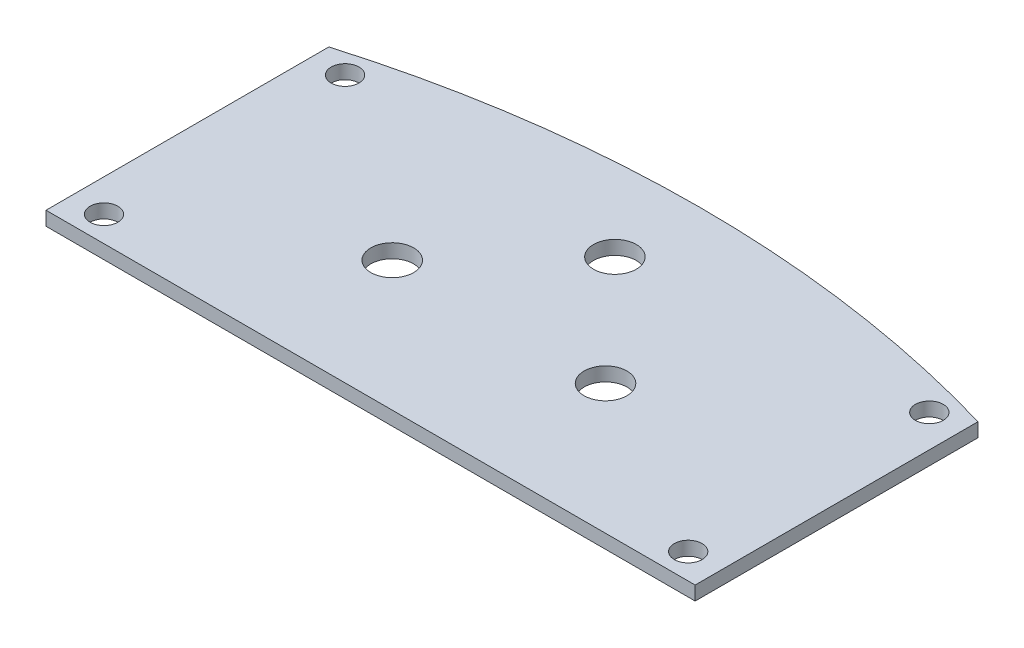
SolidWorks part; units mm, degrees
ref_plane "Front Plane" through (0, 0, 0) normal (0, 0, 1) x (1, 0, 0)
ref_plane "Top Plane" through (0, 0, 0) normal (0, 1, 0) x (1, 0, 0)
ref_plane "Right Plane" through (0, 0, 0) normal (1, 0, 0) x (0, 0, -1)
sketch "Sketch1" plane through (0, 0, 0) normal (0, 1, 0) x (1, 0, 0)
  line L1 (70, 28.5) -> (70, -32.5)
  line L3 (-70, -32.5) -> (-70, 28.5)
  line L4 (-70, -32.5) -> (70, -32.5)
  arc A0 (-70, 28.5) -> (70, 28.5) centre (0, -210.1566) cw
  dimension "D1" = 61
  dimension "D2" = 140
  dimension "D3" = 61
  dimension "D4" = 70
extrude "Boss-Extrude1" add sketch "Sketch1" along normal blind 3
sketch "Sketch3" plane through (0, 3, 0) normal (0, 1, 0) x (1, 0, 0)
  line L0 (0, 43.0385) -> (0, -46.4553) construction
  line L1 (-70, -32.5) -> (70, -32.5) construction
  circle A13 centre (-63, 25) radius 3
  circle A14 centre (-63, -27) radius 3
  circle A15 centre (63, 25) radius 3
  circle A16 centre (63, -27) radius 3
  dimension "D13" = 89.4937
  dimension "D15" = 52
  dimension "D16" = 52
  dimension "D2" = 5.5
extrude "Cut-Extrude1" cut sketch "Sketch3" against normal blind 10
sketch "Sketch4" plane through (0, 0, 0) normal (0, -1, 0) x (-1, 0, 0)
  line L0 (70, -32.5) -> (-70, -32.5) construction
  line L1 (70, 28.5) -> (70, -32.5) construction
  circle A0 centre (23.33, -4.5) radius 4.62
  circle A1 centre (-22.67, -4.5) radius 4.62
  circle A2 centre (-0.056, 20.1385) radius 4.62
  point P10 (0, 0)
  dimension "D1" = 9.24
  dimension "D2" = 28
  dimension "D4" = 46
  dimension "D5" = 33.97
  dimension "D3" = 46.67
extrude "Cut-Extrude2" cut sketch "Sketch4" against normal blind 10
